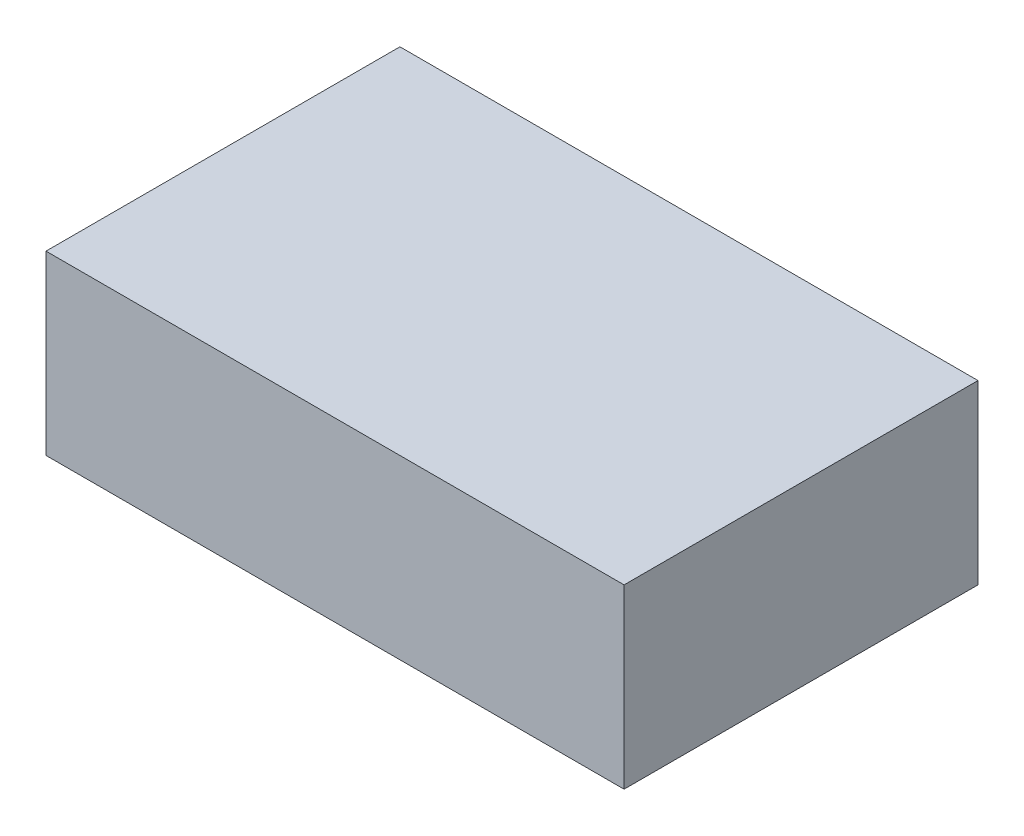
SolidWorks part; units mm, degrees
ref_plane "前视基准面" through (0, 0, 0) normal (0, 0, 1) x (1, 0, 0)
ref_plane "上视基准面" through (0, 0, 0) normal (0, 1, 0) x (1, 0, 0)
ref_plane "右视基准面" through (0, 0, 0) normal (1, 0, 0) x (0, 0, -1)
other "Configuration Table"
sketch "草图1" plane through (0, 0, 0) normal (0, 1, 0) x (1, 0, 0)
  line L1 (-49, -30) -> (49, -30)
  line L2 (-49, -30) -> (-49, 30)
  line L3 (-49, 30) -> (49, 30)
  line L4 (49, -30) -> (49, 30)
  line L5 (-49, -30) -> (49, 30) construction
  line L6 (-49, 30) -> (49, -30) construction
  point P0 (0, 0)
  dimension "D1" = 98
  dimension "D2" = 60
extrude "凸台-拉伸1" add sketch "草图1" along normal blind 30
